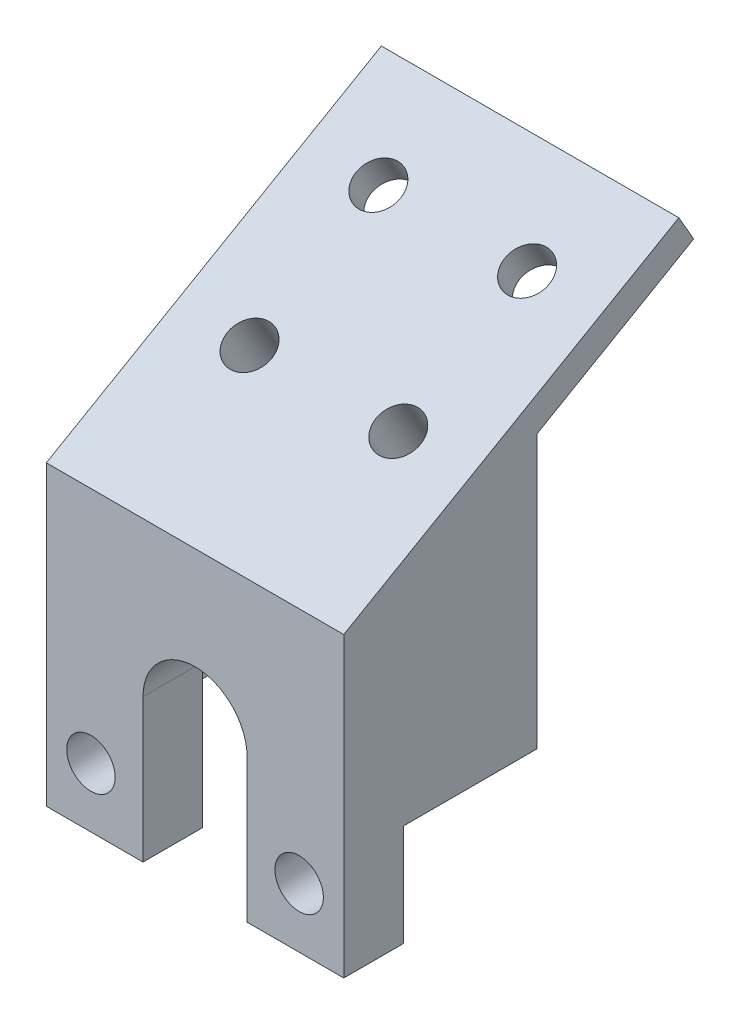
SolidWorks part; units mm, degrees
ref_plane "Alzado" through (0, 0, 0) normal (0, 0, 1) x (1, 0, 0)
ref_plane "Planta" through (0, 0, 0) normal (0, 1, 0) x (1, 0, 0)
ref_plane "Vista lateral" through (0, 0, 0) normal (1, 0, 0) x (0, 0, -1)
sketch "Croquis1" plane through (0, 0, 0) normal (0, 0, 1) x (1, 0, 0)
  line L1 (-79.0345, 42.2856) -> (-79.0345, 34.2856)
  line L3 (-99.0345, 34.2856) -> (-99.0345, 42.2856)
  line L4 (-96.0345, 39.9136) -> (-82.0345, 39.9136) construction
  line L5 (-89.0345, 39.9136) -> (-89.0345, 43.9136) construction
  line L6 (-79.0345, 42.2856) -> (-79.0345, 54.2856)
  line L7 (-79.0345, 54.2856) -> (-99.0345, 54.2856)
  line L8 (-99.0345, 54.2856) -> (-99.0345, 42.2856)
  line L9 (-89.0345, 34.2856) -> (-85.5345, 34.2856) construction
  line L10 (-89.0345, 34.2856) -> (-92.5345, 34.2856) construction
  line L13 (-79.0345, 34.2856) -> (-85.5345, 34.2856)
  line L16 (-92.5345, 34.2856) -> (-99.0345, 34.2856)
  line L17 (-85.5345, 34.2856) -> (-85.5345, 43.9136)
  line L18 (-92.5345, 34.2856) -> (-92.5345, 43.9136)
  circle A0 centre (-96.0345, 38.2856) radius 1.628
  circle A1 centre (-82.0345, 38.2856) radius 1.628
  arc A7 (-85.5345, 43.9136) -> (-92.5345, 43.9136) centre (-89.0345, 43.9136) ccw
  dimension "D1" = 14
  dimension "D2" = 20
  dimension "D3" = 8
  dimension "D4" = 3
extrude "Saliente-Extruir1" add sketch "Croquis1" along normal blind 4
sketch "Croquis2" plane through (0, 0, 0) normal (0, 0, -1) x (-1, 0, 0)
  line L0 (79.0345, 41.132) -> (83.7182, 41.132)
  line L1 (79.0345, 34.2856) -> (79.0345, 54.2856) construction
  line L2 (94.3507, 41.132) -> (99.0345, 41.132)
  line L3 (99.0345, 54.2856) -> (99.0345, 34.2856) construction
  line L4 (89.0345, 49.9136) -> (89.0345, 54.2856) construction
  line L5 (79.0345, 54.2856) -> (99.0345, 54.2856) construction
  line L6 (89.0345, 54.2856) -> (85.0345, 54.2856) construction
  line L7 (79.0345, 41.132) -> (79.0345, 54.2856)
  line L8 (79.0345, 54.2856) -> (99.0345, 54.2856)
  line L9 (99.0345, 54.2856) -> (99.0345, 41.132)
  arc A2 (83.7182, 41.132) -> (94.3507, 41.132) centre (89.0345, 43.9136) cw
extrude "Saliente-Extruir2" add sketch "Croquis2" along normal blind 9
sketch "Croquis10" plane through (0, 0, -9) normal (0, 0, -1) x (-1, 0, 0)
  line L0 (99.0345, 54.2856) -> (93.9712, 54.2856) construction
  line L1 (99.0345, 54.2856) -> (79.0345, 54.2856) construction
  line L2 (99.0345, 41.132) -> (99.0345, 54.2856) construction
  line L3 (79.0345, 54.2856) -> (79.0345, 41.132) construction
  line L4 (79.0345, 41.132) -> (83.7182, 41.132) construction
  circle A0 centre (96.5345, 51.7856) radius 1
  circle A1 centre (81.0345, 43.132) radius 1
  dimension "D1" = 2.5
  dimension "D2" = 2.5
  dimension "D3" = 2
  dimension "D4" = 2
extrude "Cortar-Extruir3" cut sketch "Croquis10" against normal blind 4
sketch "Croquis11" plane through (-99.0345, 0, 0) normal (-1, 0, 0) x (0, 0, 1)
  line L0 (-9, 54.2856) -> (-9, 61.7912)
  line L1 (-9, 61.7912) -> (4, 54.2856)
  line L2 (4, 54.2856) -> (-9, 54.2856)
  dimension "D1" = 30
extrude "Saliente-Extruir3" add sketch "Croquis11" against normal up to vertex (20 mm away)
sketch "Croquis16" plane through (-99.0345, 0, 0) normal (-1, 0, 0) x (0, 0, 1)
  line L0 (-9, 61.7912) -> (-21.9904, 69.2912)
  line L1 (-21.9904, 69.2912) -> (-22.9904, 67.5591)
  line L2 (-22.9904, 67.5591) -> (-9, 59.4818)
  line L3 (-9, 41.132) -> (-9, 61.7912) construction
  line L4 (-9, 59.4818) -> (-9, 61.7912)
extrude "Saliente-Extruir4" add sketch "Croquis16" against normal up to vertex (20 mm away)
sketch "Croquis17" plane through (0, 42.4463, 24.5064) normal (0, 0.866, 0.5) x (1, 0, 0)
  line L0 (-79.0345, 53.6898) -> (-99.0345, 23.6787) construction
  line L1 (-89.0345, 23.6787) -> (-89.0345, 38.6843) construction
  line L2 (-79.0345, 23.6787) -> (-99.0345, 23.6787) construction
  line L3 (-89.0345, 38.6843) -> (-84.0345, 38.6843) construction
  line L4 (-84.0345, 38.6843) -> (-84.0345, 33.6843) construction
  circle A0 centre (-84.0345, 33.6843) radius 1.5
  circle A1 centre (-94.0345, 33.6843) radius 1.5
  circle A2 centre (-94.0345, 43.6843) radius 1.5
  circle A3 centre (-84.0345, 43.6843) radius 1.5
  dimension "D1" = 2
  dimension "D2" = 2
extrude "Cortar-Extruir6" cut sketch "Croquis17" against normal blind 4
sketch "Croquis19" plane through (0, 42.4463, 24.5064) normal (0, 0.866, 0.5) x (1, 0, 0)
  line L0 (-79.0345, 23.6787) -> (-79.0345, 53.6898) construction
  line L1 (-99.0345, 53.6898) -> (-79.0345, 53.6898)
  line L2 (-99.0345, 53.6898) -> (-99.0345, 49.6898)
  line L3 (-99.0345, 49.6898) -> (-79.0345, 49.6898)
  line L4 (-79.0345, 53.6898) -> (-79.0345, 49.6898)
  dimension "D1" = 4
extrude "Cortar-Extruir7" cut sketch "Croquis19" against normal blind 2
